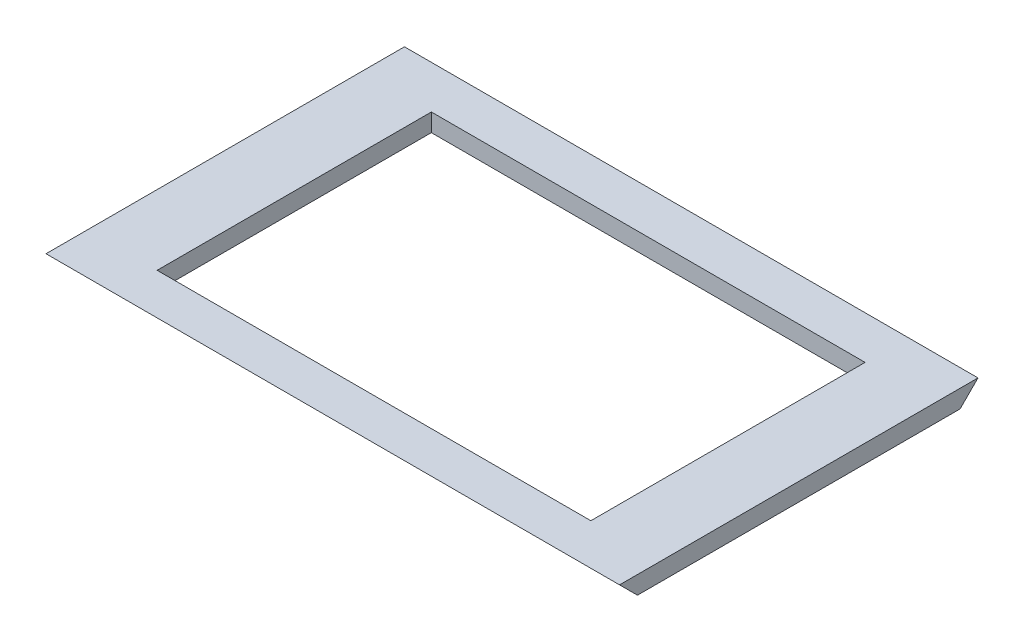
SolidWorks part; units mm, degrees
material "PVC Rigid"
ref_plane "Front Plane" through (0, 0, 0) normal (0, 0, 1) x (1, 0, 0)
ref_plane "Top Plane" through (0, 0, 0) normal (0, 1, 0) x (1, 0, 0)
ref_plane "Right Plane" through (0, 0, 0) normal (1, 0, 0) x (0, 0, -1)
sketch "Sketch1" plane through (0, 0, 0) normal (1, 0, 0) x (0, 0, -1)
  line L1 (-50, 2.5) -> (50, 2.5)
  line L2 (-50, 2.5) -> (-50, -2.5)
  line L3 (-50, -2.5) -> (50, -2.5)
  line L4 (50, 2.5) -> (50, -2.5)
  dimension "D1" = 100
  dimension "D2" = 5
  dimension "D3" = 2.5
  dimension "D4" = 50
extrude "Boss-Extrude1" add sketch "Sketch1" along normal blind 300
sketch "Sketch2" plane through (300, 0, 0) normal (1, 0, 0) x (0, 0, -1)
  line L0 (-50, 2.5) -> (-45, -2.5)
  line L1 (-50, -2.5) -> (50, -2.5) construction
  line L2 (-45, -2.5) -> (-50, -2.5)
  line L3 (-50, -2.5) -> (-50, 2.5)
  dimension "D1" = 5
extrude "Cut-Extrude1" cut sketch "Sketch2" against normal blind 300
sketch "Sketch3" plane through (0, 2.5, 0) normal (0, 1, 0) x (1, 0, 0)
  line L0 (0, 50) -> (0, -50) construction
  line L1 (89.5, 38) -> (210.5, 38)
  line L2 (89.5, 38) -> (89.5, -38.5)
  line L3 (89.5, -38.5) -> (210.5, -38.5)
  line L4 (210.5, 38) -> (210.5, -38.5)
  line L5 (300, 50) -> (0, 50) construction
  dimension "D1" = 121
  dimension "D2" = 76.5
  dimension "D3" = 89.5
  dimension "D4" = 12
extrude "Cut-Extrude2" cut sketch "Sketch3" against normal blind 5
sketch "Sketch4" plane through (300, 0, 0) normal (1, 0, 0) x (0, 0, -1)
  line L0 (50, 2.5) -> (45, -2.5)
  line L1 (-45, -2.5) -> (50, -2.5) construction
  line L2 (45, -2.5) -> (50, -2.5)
  line L3 (50, -2.5) -> (50, 2.5) construction
  line L4 (50, -2.5) -> (50, 2.5)
  dimension "D1" = 5
extrude "Cut-Extrude3" cut sketch "Sketch4" against normal blind 300
sketch "Sketch5" plane through (0, 2.5, 0) normal (0, 1, 0) x (1, 0, 0)
  line L0 (300, -50) -> (0, -50) construction
  line L6 (0, 50) -> (70, 50)
  line L7 (0, 50) -> (0, -50)
  line L8 (0, -50) -> (70, -50)
  line L9 (70, 50) -> (70, -50)
  line L10 (300, 50) -> (230, 50)
  line L11 (300, 50) -> (300, -50)
  line L12 (300, -50) -> (230, -50)
  line L13 (230, 50) -> (230, -50)
  dimension "D1" = 70
  dimension "D3" = 70
extrude "Cut-Extrude4" cut sketch "Sketch5" against normal blind 5
